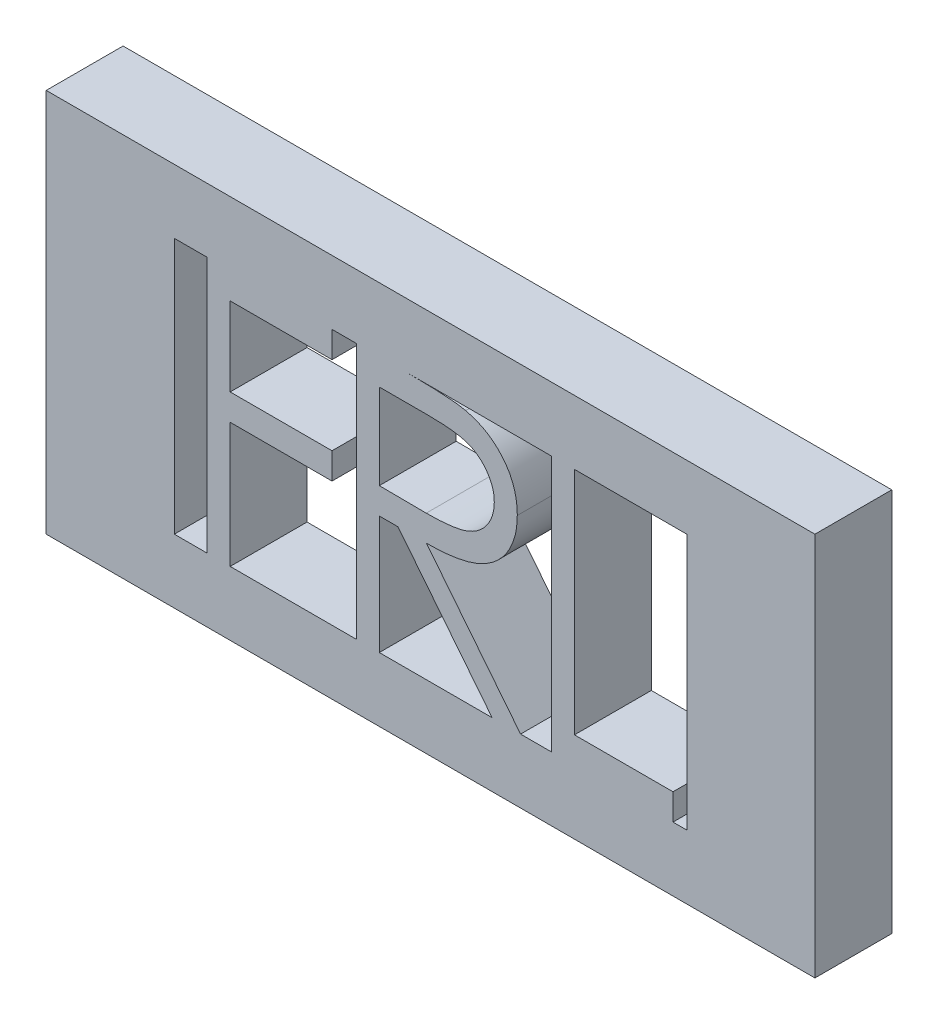
SolidWorks part; units mm, degrees
ref_plane "Front Plane" through (0, 0, 0) normal (0, 0, 1) x (1, 0, 0)
ref_plane "Top Plane" through (0, 0, 0) normal (0, 1, 0) x (1, 0, 0)
ref_plane "Right Plane" through (0, 0, 0) normal (1, 0, 0) x (0, 0, -1)
sketch "Sketch1" plane through (0, 0, 0) normal (0, 0, 1) x (1, 0, 0)
  line L1 (-15, 7.5) -> (15, 7.5)
  line L2 (-15, 7.5) -> (-15, -7.5)
  line L3 (-15, -7.5) -> (15, -7.5)
  line L4 (15, 7.5) -> (15, -7.5)
  line L5 (-15, 7.5) -> (15, -7.5) construction
  line L6 (-15, -7.5) -> (15, 7.5) construction
  point P0 (0, 0)
  dimension "D1" = 15
  dimension "D2" = 30
extrude "Boss-Extrude1" add sketch "Sketch1" along normal blind 3
sketch "Sketch2" plane through (0, 0, 3) normal (0, 0, 1) x (1, 0, 0)
  line L1 (-10, 5) -> (10, 5)
  line L2 (-10, 5) -> (-10, -5)
  line L3 (-10, -5) -> (10, -5)
  line L4 (10, 5) -> (10, -5)
  line L5 (-10, 5) -> (10, -5) construction
  line L6 (-10, -5) -> (10, 5) construction
  point P0 (0, 0)
  dimension "D1" = 20
  dimension "D2" = 10
extrude "Cut-Extrude1" cut sketch "Sketch2" against normal through all
sketch "Sketch3" plane through (0, 0, 3) normal (0, 0, 1) x (1, 0, 0)
  text T0 "FRL" font "Century Gothic" height 10
extrude "Boss-Extrude2" add sketch "Sketch3" against normal blind 3
